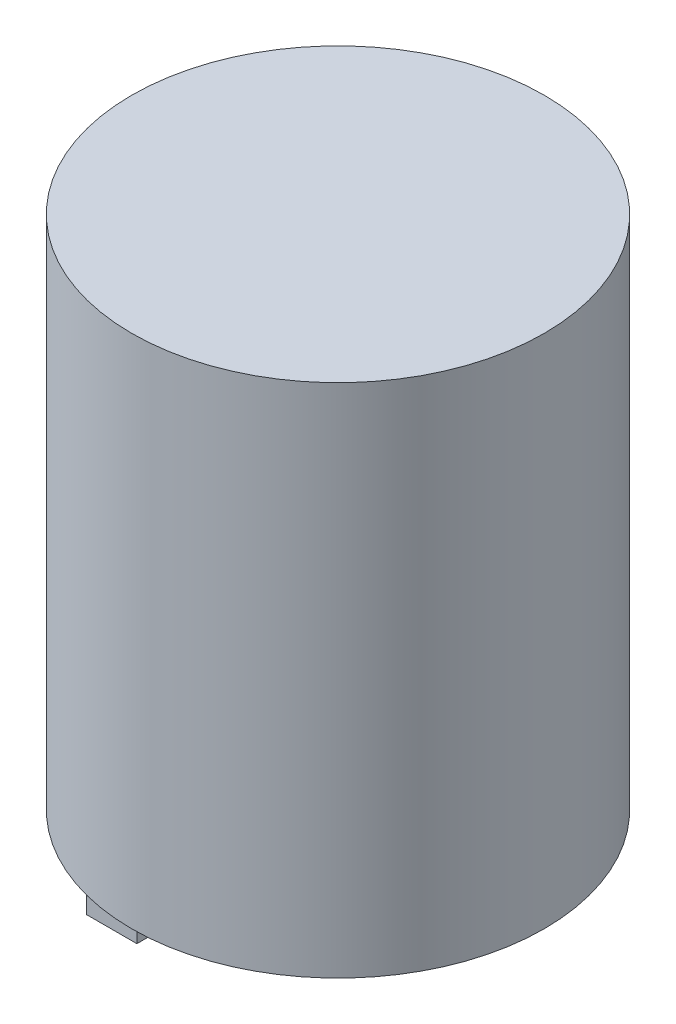
SolidWorks part; units mm, degrees
ref_plane "Front Plane" through (0, 0, 0) normal (0, 0, 1) x (1, 0, 0)
ref_plane "Top Plane" through (0, 0, 0) normal (0, 1, 0) x (1, 0, 0)
ref_plane "Right Plane" through (0, 0, 0) normal (1, 0, 0) x (0, 0, -1)
sketch "Sketch1" plane through (0, 0, 0) normal (0, 1, 0) x (1, 0, 0)
  circle A0 centre (0, 0) radius 10
  dimension "D1" = 20
extrude "Boss-Extrude1" add sketch "Sketch1" along normal blind 25
sketch "Sketch2" plane through (0, 0, 0) normal (0, -1, 0) x (-1, 0, 0)
  line L1 (8.5, 2.5) -> (7.25, 2.5)
  line L2 (8.5, 2.5) -> (8.5, -2.5)
  line L3 (8.5, -2.5) -> (7.25, -2.5)
  line L4 (7.25, 2.5) -> (7.25, -2.5)
  point P4 (7.25, 0)
  dimension "D1" = 5
  dimension "D2" = 1.25
  dimension "D3" = 7.25
extrude "Boss-Extrude2" add sketch "Sketch2" along normal blind 8 separate body
sketch "Sketch3" plane through (-8.5, 0, 0) normal (-1, 0, 0) x (0, 0, 1)
  line L0 (-2.5, -8) -> (-2.5, 0)
  line L1 (-2.5, 0) -> (2.5, 0)
  line L2 (2.5, 0) -> (2.5, -8)
  line L3 (2.5, -8) -> (1.5, -8)
  line L4 (2.5, -8) -> (-2.5, -8) construction
  line L5 (1.5, -8) -> (1.5, -0.75)
  line L6 (1.5, -0.75) -> (-1.5, -0.75)
  line L7 (-1.5, -0.75) -> (-1.5, -8)
  line L8 (-1.5, -8) -> (-2.5, -8)
  dimension "D1" = 1
  dimension "D2" = 1
  dimension "D3" = 0.75
extrude "Boss-Extrude3" add sketch "Sketch3" along normal blind 1.2
